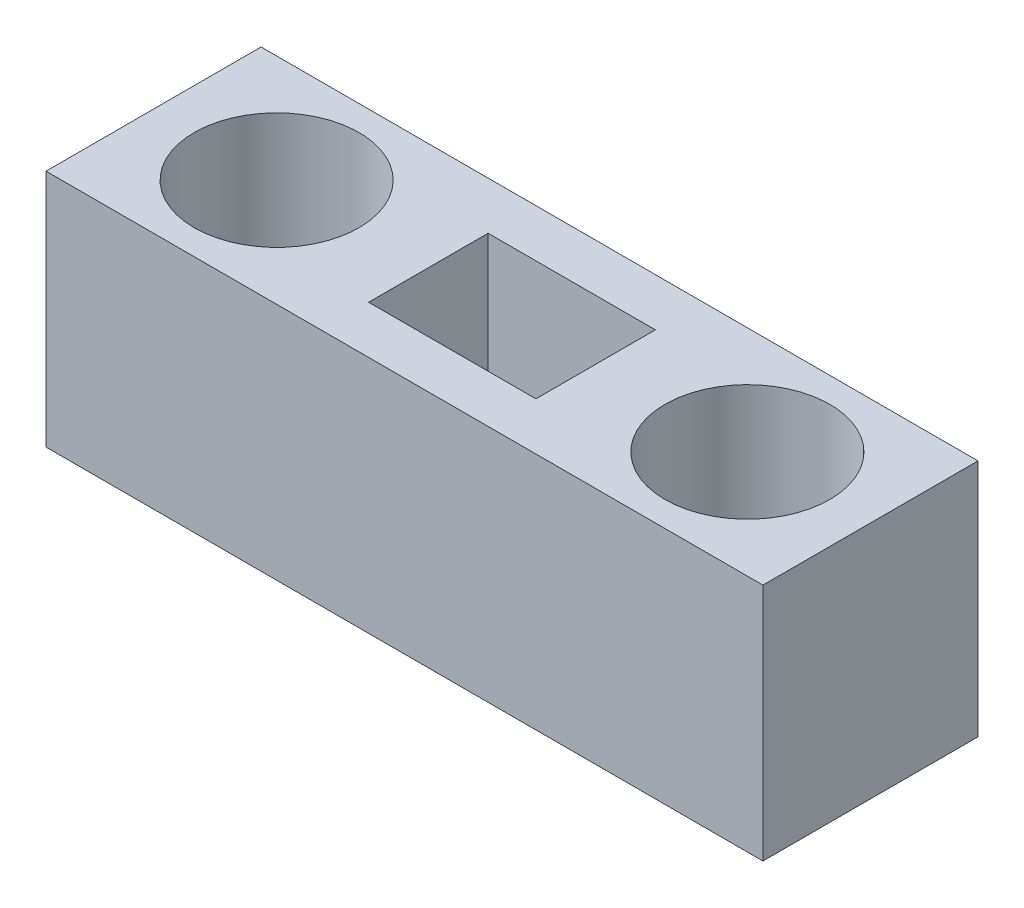
SolidWorks part; units mm, degrees
ref_plane "Front Plane" through (0, 0, 0) normal (0, 0, 1) x (1, 0, 0)
ref_plane "Top Plane" through (0, 0, 0) normal (0, 1, 0) x (1, 0, 0)
ref_plane "Right Plane" through (0, 0, 0) normal (1, 0, 0) x (0, 0, -1)
sketch "Sketch1" plane through (0, 0, 0) normal (0, 1, 0) x (1, 0, 0)
  line L0 (-9.85, 0) -> (9.85, 0) construction
  line L1 (-15, -4.5) -> (15, -4.5)
  line L2 (-15, -4.5) -> (-15, 4.5)
  line L3 (-15, 4.5) -> (15, 4.5)
  line L4 (15, -4.5) -> (15, 4.5)
  line L5 (-15, -4.5) -> (15, 4.5) construction
  line L6 (-15, 4.5) -> (15, -4.5) construction
  line L8 (-3.5, -2.5) -> (3.5, -2.5)
  line L9 (-3.5, -2.5) -> (-3.5, 2.5)
  line L10 (-3.5, 2.5) -> (3.5, 2.5)
  line L11 (3.5, -2.5) -> (3.5, 2.5)
  line L12 (-3.5, -2.5) -> (3.5, 2.5) construction
  line L13 (-3.5, 2.5) -> (3.5, -2.5) construction
  circle A0 centre (-9.85, 0) radius 3.45
  circle A1 centre (9.85, 0) radius 3.45
  point P0 (0, 0)
  point P9 (0, 0)
  point P11 (0, 0)
  dimension "D1" = 30
  dimension "D3" = 6.9
  dimension "D5" = 6.9
  dimension "D2" = 9
  dimension "D4" = 19.7
  dimension "D6" = 7
  dimension "D7" = 5
extrude "Boss-Extrude1" add sketch "Sketch1" along normal blind 10
